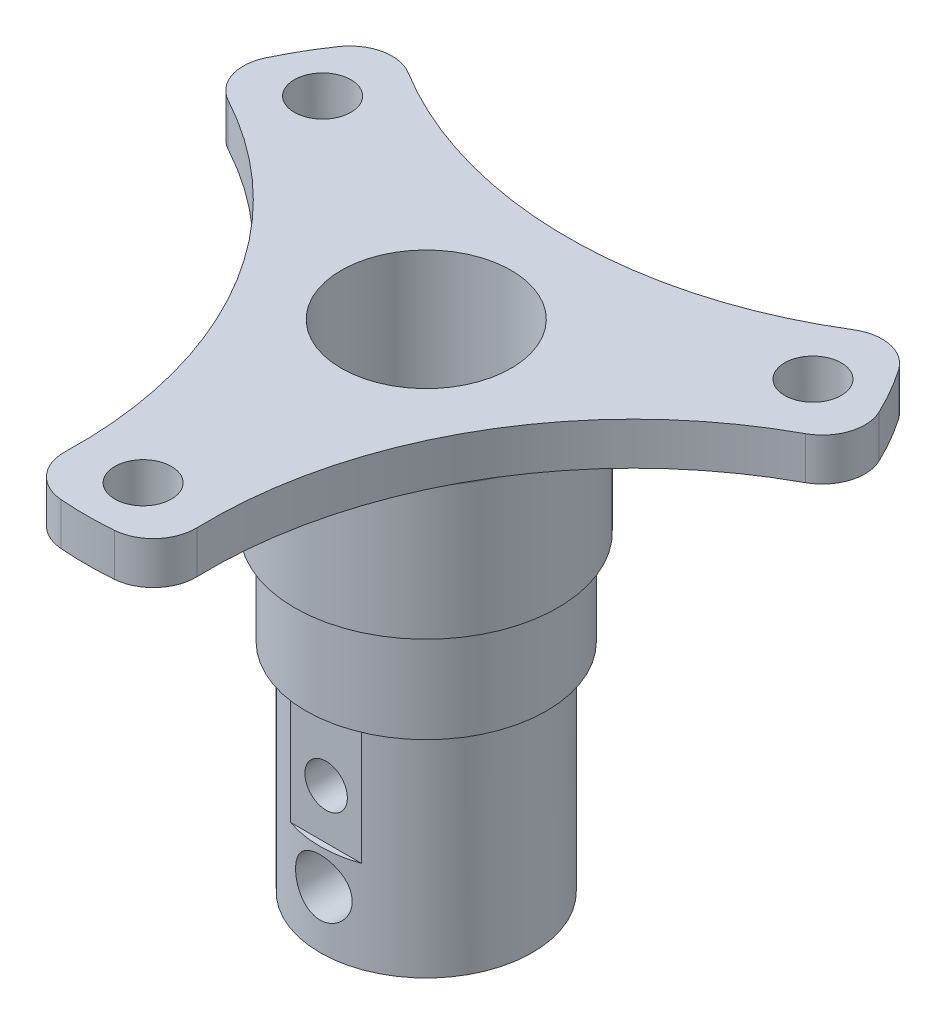
SolidWorks part; units mm, degrees
material "合金钢"
ref_plane "前视基准面" through (0, 0, 0) normal (0, 0, 1) x (1, 0, 0)
ref_plane "上视基准面" through (0, 0, 0) normal (0, 1, 0) x (1, 0, 0)
ref_plane "右视基准面" through (0, 0, 0) normal (1, 0, 0) x (0, 0, -1)
sketch "草图2" plane through (0, 0, 0) normal (0, 0, 1) x (1, 0, 0)
  line L0 (0, 41.0598) -> (0, -36.782) construction
  line L1 (-48.5969, 0) -> (54.3933, 0) construction
  line L24 (-7.5, 0) -> (-7.5, 15)
  line L25 (-7.5, 15) -> (-8.5, 15)
  line L26 (-8.5, 15) -> (-8.5, 22)
  line L27 (-8.5, 22) -> (-9.3, 22)
  line L28 (-9.3, 22) -> (-9.3, 32)
  line L29 (-9.3, 32) -> (-24, 32)
  line L30 (-24, 32) -> (-24, 35)
  line L31 (-24, 35) -> (-8, 35)
  line L32 (-8, 35) -> (-8, 40)
  line L33 (-8, 40) -> (-5, 40)
  line L34 (-5, 40) -> (-5, 0) construction
  line L35 (-5, 0) -> (-7.5, 0)
  line L36 (-5, 40) -> (0, 40)
  line L37 (0, 40) -> (0, 0)
  line L38 (0, 0) -> (-5, 0)
  dimension "D1" = 5
  dimension "D2" = 15
  dimension "D3" = 17
  dimension "D4" = 15
  dimension "D5" = 18.6
  dimension "D6" = 3
  dimension "D7" = 48
  dimension "D8" = 10
  dimension "D9" = 7
  dimension "D10" = 16
  dimension "D11" = 5
revolve "旋转1" add sketch "草图2" angle 360 about L0
sketch "草图3" plane through (0, 0, 0) normal (0, -1, 0) x (1, 0, 0)
  line L0 (-3, 4) -> (3, 4)
  arc A0 (-3, 4) -> (3, 4) centre (0, 0) ccw
  dimension "D2" = 10
  dimension "D1" = 4
extrude "切除-拉伸1" cut sketch "草图3" against normal blind 20
sketch "草图4" plane through (0, 32, 0) normal (0, -1, 0) x (1, 0, 0)
  line L0 (0, 0) -> (0, -42.2676) construction
  circle A0 centre (0, 20) radius 2
  arc A1 (-3, 4) -> (3, 4) centre (0, 0) ccw construction
  circle A2 centre (17.3205, -10) radius 2
  circle A3 centre (-17.3205, -10) radius 2
  circle A4 centre (0, -40) radius 30
  circle A5 centre (0, 0) radius 9.3 construction
  circle A6 centre (-34.641, 20) radius 30
  circle A7 centre (34.641, 20) radius 30
  point P13 (0, 0)
  point P25 (0, 0)
  dimension "D1" = 4
  dimension "D2" = 20
  dimension "D4" = 2.641
  dimension "D5" = 40
  dimension "D6" = 60
  dimension "D7" = 0.7
  dimension "D3" = 3
  dimension "D8" = 3
extrude "切除-拉伸2" cut sketch "草图4" against normal through all
chamfer "倒角1" [suppressed] distance 2 angle 45
fillet "圆角1" radius 3 6 edges at (22.7797, 33.5, -7.5556) (4.8465, 33.5, 23.5056) (-17.9331, 33.5, -15.95) (17.9331, 33.5, -15.95) (-4.8465, 33.5, 23.5056) (-22.7797, 33.5, -7.5556)
sketch "草图5" plane through (0, 0, 0) normal (0, 0, 1) x (1, 0, 0)
  line L0 (0, 0) -> (0, 38.8914) construction
  line L1 (-7.5, 0) -> (7.5, 0) construction
  circle A0 centre (0, 4) radius 2
  circle A1 centre (0, 10) radius 1.5
  dimension "D1" = 3
  dimension "D2" = 4
  dimension "D3" = 10
  dimension "D4" = 6
  dimension "D5" = 4
extrude "切除-拉伸3" cut sketch "草图5" along normal blind 20
sketch "草图8" plane through (0, 15, 0) normal (0, -1, 0) x (1, 0, 0)
  line L0 (-2.5, 7.0711) -> (2.5, 7.0711)
  line L1 (-2.5, -7.0711) -> (2.5, -7.0711)
  circle A0 centre (0, 0) radius 7.5 construction
  arc A1 (2.5, 7.0711) -> (-2.5, 7.0711) centre (0, 0) ccw
  arc A2 (-2.5, -7.0711) -> (2.5, -7.0711) centre (0, 0) ccw
  dimension "D1" = 5
  dimension "D2" = 5
extrude "切除-拉伸5" cut sketch "草图8" along normal blind 8.5
sketch "草图9" plane through (0, 0, 7.0711) normal (0, 0, 1) x (1, 0, 0)
  circle A0 centre (0, 10) radius 1.5
  dimension "D1" = 3
extrude "切除-拉伸6" cut sketch "草图9" against normal through all
sketch "草图11" plane through (0, 40, 0) normal (0, 1, 0) x (1, 0, 0)
  circle A0 centre (0, 0) radius 8 construction
  circle A1 centre (0, 0) radius 8
extrude "切除-拉伸8" cut sketch "草图11" against normal up to surface (5 mm away) up to face at (-17.3205, 35, -8)
hole_wizard "Ø12.0 (12) 直径孔1" positions "3D草图1" profile "草图13" hole size "Ø12.0" standard "GB"
sketch3d "3D草图1"
  line L0 (0, 32, 0) -> (0, 35, 0) construction
  point P0 (0, 35, 0)
sketch "草图13" plane through (0, 35, 0) normal (1, 0, 0) x (0, 0, 1)
  line L0 (0, 0) -> (0, 13.6052)
  line L1 (0, 13.6052) -> (6, 10)
  line L2 (6, 10) -> (6, 0)
  line L5 (6, 0) -> (0, 0)
  line L10 (0, 13.6052) -> (-6, 10) construction
  line L11 (0, -6.35) -> (0, 107.95) construction
  dimension "孔直径" = 12
  dimension "孔深度" = 10
  dimension "导头角度" = 118
fillet "圆角2" radius 0.6 1 edges at (0, 32, 9.3)
chamfer "倒角2" distance 0.5 angle 30 1 edges at (0, 15, 8.5)
chamfer "倒角3" distance 0.5 angle 30 1 edges at (0, 0, -5)
